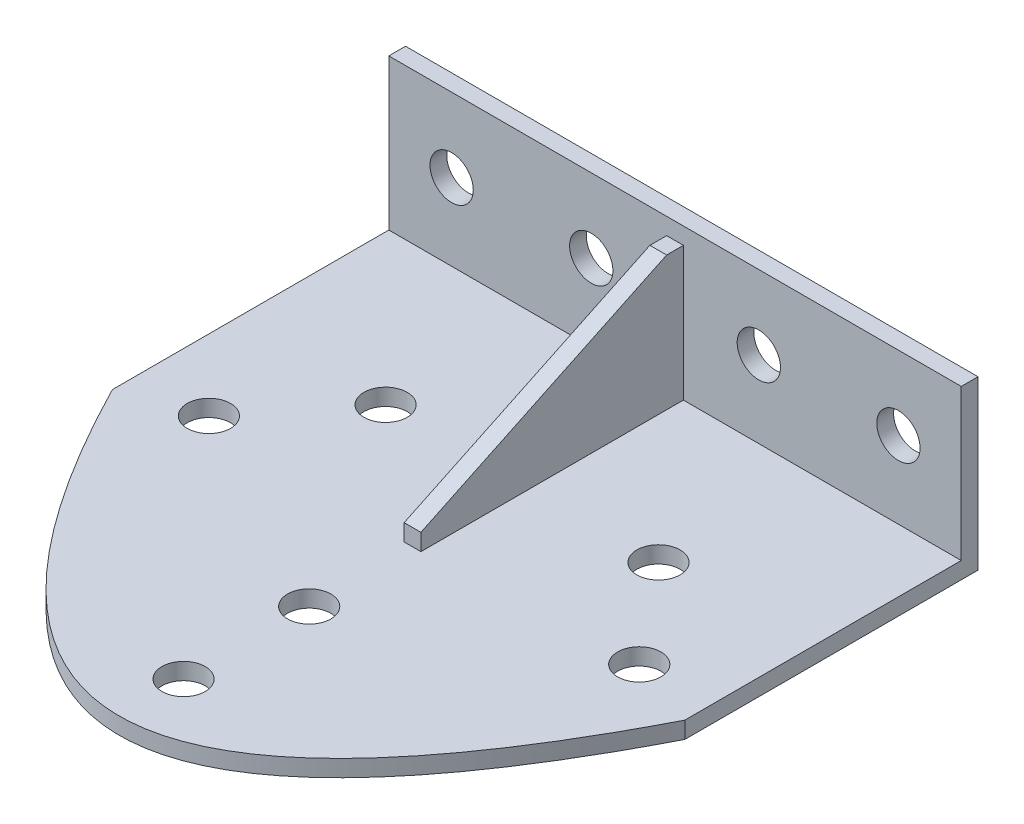
SolidWorks part; units mm, degrees
ref_plane "Front Plane" through (0, 0, 0) normal (0, 0, 1) x (1, 0, 0)
ref_plane "Top Plane" through (0, 0, 0) normal (0, 1, 0) x (1, 0, 0)
ref_plane "Right Plane" through (0, 0, 0) normal (1, 0, 0) x (0, 0, -1)
sketch "Sketch1" plane through (0, 0, 0) normal (0, 0, 1) x (1, 0, 0)
  line L1 (0, 0) -> (410, 0)
  line L2 (0, 0) -> (0, 120)
  line L3 (0, 120) -> (410, 120)
  line L4 (410, 0) -> (410, 120)
  circle A0 centre (45, 67) radius 15.5
  circle A1 centre (145, 67) radius 15.5
  circle A2 centre (365, 67) radius 15.5
  circle A3 centre (265, 67) radius 15.5
  dimension "D3" = 31
  dimension "D7" = 31
  dimension "D9" = 31
  dimension "D13" = 31
  dimension "D1" = 120
  dimension "D2" = 410
  dimension "D4" = 45
  dimension "D5" = 67
  dimension "D6" = 100
  dimension "D8" = 67
  dimension "D10" = 67
  dimension "D11" = 120
  dimension "D12" = 100
  dimension "D14" = 67
extrude "Extrude1" add sketch "Sketch1" along normal blind 12
sketch "Sketch2" plane through (0, 0, 12) normal (0, 0, 1) x (1, 0, 0)
  line L0 (410, 0) -> (410, 120) construction
  line L1 (0, 0) -> (410, 0)
  line L2 (0, 0) -> (0, 12)
  line L3 (0, 12) -> (410, 12)
  line L4 (410, 0) -> (410, 12)
  dimension "D1" = 12
extrude "Extrude2" add sketch "Sketch2" along normal blind 398
sketch "Sketch3" plane through (0, 12, 0) normal (0, 1, 0) x (1, 0, 0)
  line L0 (205, 0) -> (205, -410) construction
  line L1 (410, 0) -> (0, 0) construction
  line L2 (410, -410) -> (0, -410) construction
  line L3 (205, 0) -> (205, -2488) construction
  line L4 (205, -2488) -> (2205, -2488) construction
  line L5 (2205, -2488) -> (205, 0) construction
  line L6 (0, -410) -> (0, -12) construction
  line L7 (410, -410) -> (410, -12) construction
  circle A0 centre (205, -364) radius 15.5
  circle A1 centre (205, -274) radius 15.5
  circle A2 centre (302.7382, -121.5863) radius 15.5
  circle A3 centre (359.1257, -191.7323) radius 15.5
  circle A4 centre (50.8743, -191.7323) radius 15.5
  circle A5 centre (107.2618, -121.5863) radius 15.5
  spline S0 degree 2 poles (0, -210) (205, -610) (410, -210) knots 0 0 0 1 1 1
  line M2 (0, -12) -> (0, -410)
  line M3 (0, -410) -> (410, -410)
  line M4 (410, -410) -> (410, -12)
  dimension "D1" = 31
  dimension "D4" = 31
  dimension "D8" = 31
  dimension "D10" = 31
  dimension "D2" = 46
  dimension "D3" = 90
  dimension "D5" = 274
  dimension "D6" = 2000
  dimension "D7" = 2488
  dimension "D9" = 156
  dimension "D11" = 90
  dimension "D12" = 200
  dimension "D13" = 200
extrude "Extrude3" cut sketch "Sketch3" against normal blind 198 contours S0 M3 M4 | S0 M2 M3 | A5 | A0 | A4 | A1 | A3 | A2
sketch "Sketch4" plane through (0, 0, 12) normal (0, 0, 1) x (1, 0, 0)
  line L0 (410, 12) -> (0, 12) construction
  line L1 (199, 108) -> (211, 108)
  line L2 (199, 108) -> (199, 12)
  line L3 (199, 12) -> (211, 12)
  line L4 (211, 108) -> (211, 12)
  line L5 (410, 120) -> (0, 120) construction
  line L6 (410, 12) -> (410, 120) construction
  dimension "D1" = 12
  dimension "D2" = 12
  dimension "D3" = 199
extrude "Extrude4" add sketch "Sketch4" along normal blind 188
sketch "Sketch5" plane through (199, 0, 0) normal (-1, 0, 0) x (0, 0, 1)
  line L0 (200, 108) -> (200, 24)
  line L1 (200, 108) -> (200, 12) construction
  line L2 (200, 24) -> (24, 108)
  line L3 (200, 108) -> (12, 108) construction
  line L4 (24, 108) -> (200, 108)
  line L5 (210, 12) -> (12, 12) construction
  dimension "D1" = 12
  dimension "D2" = 12
extrude "Extrude5" cut sketch "Sketch5" against normal blind 188
